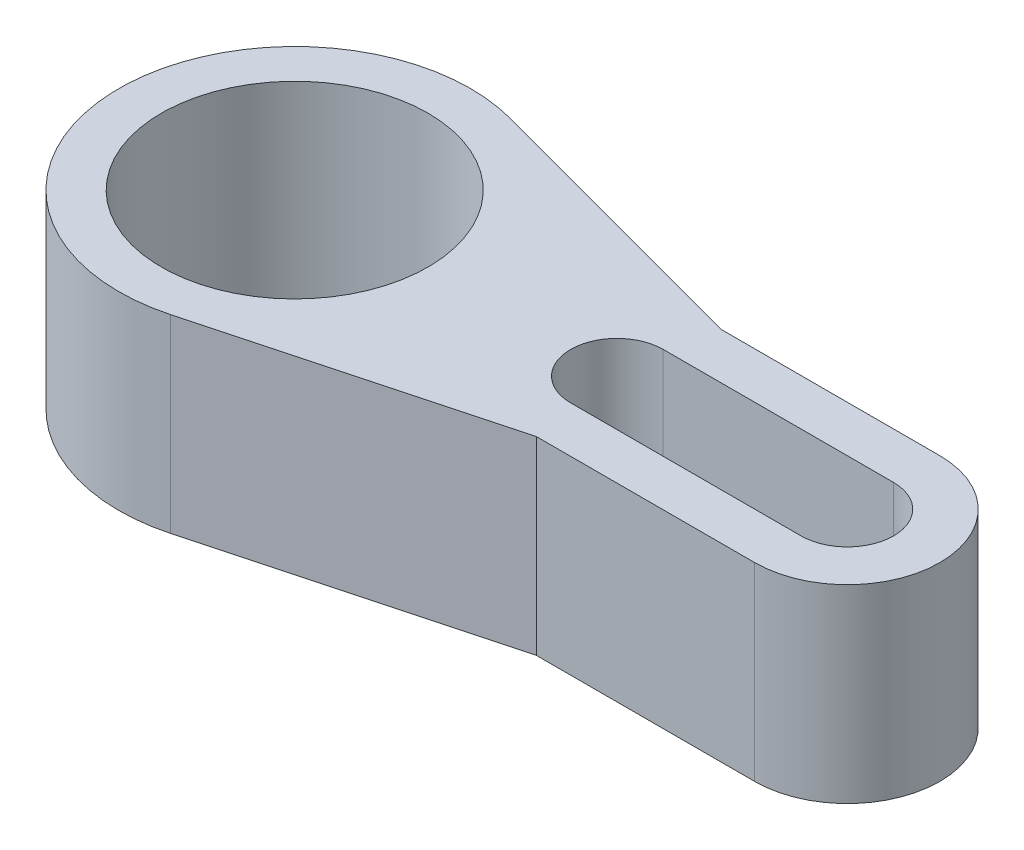
SolidWorks part; units mm, degrees
ref_plane "Front Plane" through (0, 0, 0) normal (0, 0, 1) x (1, 0, 0)
ref_plane "Top Plane" through (0, 0, 0) normal (0, 1, 0) x (1, 0, 0)
ref_plane "Right Plane" through (0, 0, 0) normal (1, 0, 0) x (0, 0, -1)
sketch "Sketch1" plane through (0, 0, 0) normal (0, 1, 0) x (1, 0, 0)
  line L0 (0, 0) -> (22.1, 0) construction
  line L1 (3.12, -11.6546) -> (23.7421, -6.134)
  line L2 (3.12, 11.6546) -> (23.7421, 6.134)
  line L3 (22.1, 0) -> (37.9, 0) construction
  line L4 (22.1, 3.175) -> (37.9, 3.175)
  line L5 (22.1, -3.175) -> (37.9, -3.175)
  line L6 (22.1, 0) -> (37.9, 0) construction
  line L7 (22.1, 6.35) -> (37.9, 6.35)
  line L8 (22.1, -6.35) -> (37.9, -6.35)
  circle A0 centre (0, 0) radius 9.145
  circle A1 centre (22.1, 0) radius 3.175
  circle A2 centre (0, 0) radius 12.065
  circle A3 centre (22.1, 0) radius 6.35
  arc A4 (22.1, 3.175) -> (22.1, -3.175) centre (22.1, 0) ccw
  arc A5 (37.9, -3.175) -> (37.9, 3.175) centre (37.9, 0) ccw
  arc A6 (22.1, 6.35) -> (22.1, -6.35) centre (22.1, 0) ccw
  arc A7 (37.9, -6.35) -> (37.9, 6.35) centre (37.9, 0) ccw
  point P12 (30, 0)
  point P17 (30, 0)
  dimension "D1" = 18.29
  dimension "D2" = 6.35
  dimension "D3" = 24.13
  dimension "D4" = 12.7
  dimension "D6" = 15.8
  dimension "D5" = 22.1
  dimension "D7" = 6.35
  dimension "D8" = 12.7
extrude "Boss-Extrude3" add sketch "Sketch1" along normal blind 13 contours A3 L7 L2 A2 L1 L8 | A3 L5 A1 L4 | L8 A7 L7 L2 A3 L4 A5 L5 L1 | A3 L2 L7 | A3 L8 L1 | A2 A0
